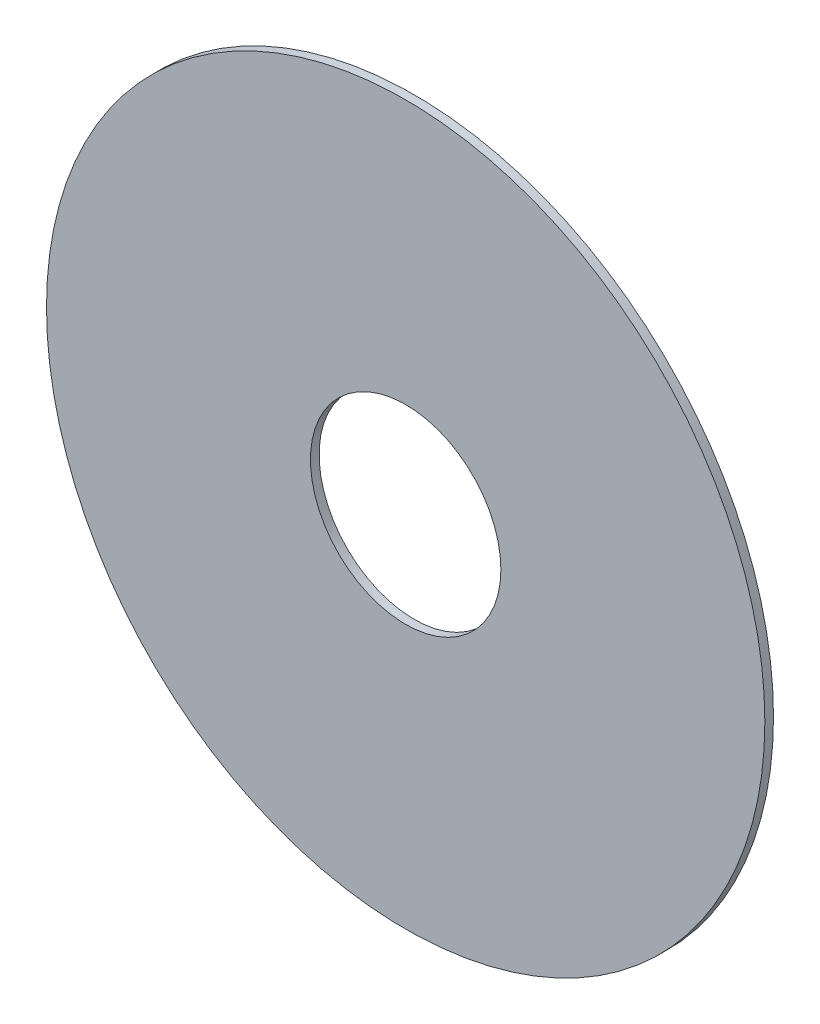
SolidWorks part; units mm, degrees
ref_plane "前视基准面" through (0, 0, 0) normal (0, 0, 1) x (1, 0, 0)
ref_plane "上视基准面" through (0, 0, 0) normal (0, 1, 0) x (1, 0, 0)
ref_plane "右视基准面" through (0, 0, 0) normal (1, 0, 0) x (0, 0, -1)
other "Configuration Table"
sketch "草图2" plane through (0, 0, 270) normal (0, 0, 1) x (1, 0, 0)
  circle A2 centre (-196.0786, 135.3771) radius 41.5
  circle A3 centre (-196.0786, 135.3771) radius 11
  dimension "D1" = 83
  dimension "D2" = 22
extrude "凸台-拉伸1" add sketch "草图2" along normal blind 1
equation "\"r_hh\"=22"
equation "\"D2@草图2\"=\"r_hh\""
